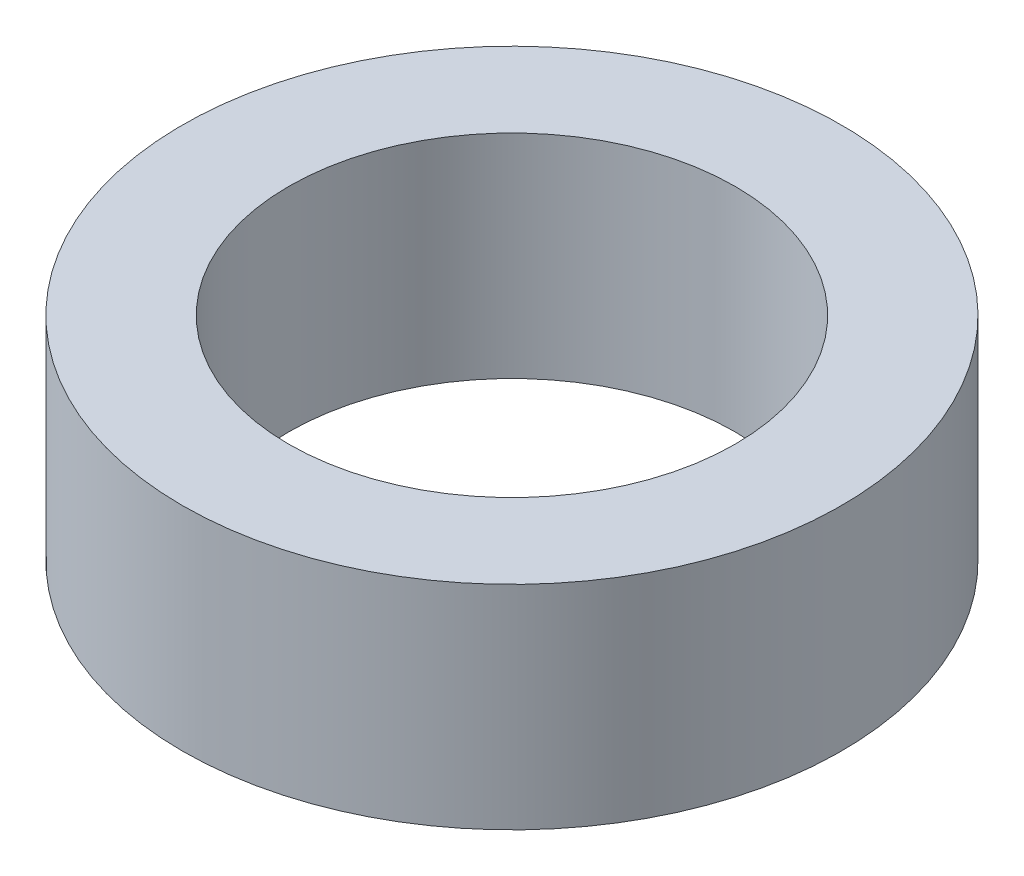
SolidWorks part; units mm, degrees
material "ABS"
ref_plane "Front Plane" through (0, 0, 0) normal (0, 0, 1) x (1, 0, 0)
ref_plane "Top Plane" through (0, 0, 0) normal (0, 1, 0) x (1, 0, 0)
ref_plane "Right Plane" through (0, 0, 0) normal (1, 0, 0) x (0, 0, -1)
sketch "Sketch1" plane through (0, 0, 0) normal (0, 1, 0) x (1, 0, 0)
  circle A0 centre (0, 0) radius 2.667
  circle A1 centre (0, 0) radius 3.937
  dimension "D1" = 5.334
  dimension "D2" = 1.27
extrude "Boss-Extrude1" add sketch "Sketch1" along normal blind 2.54
